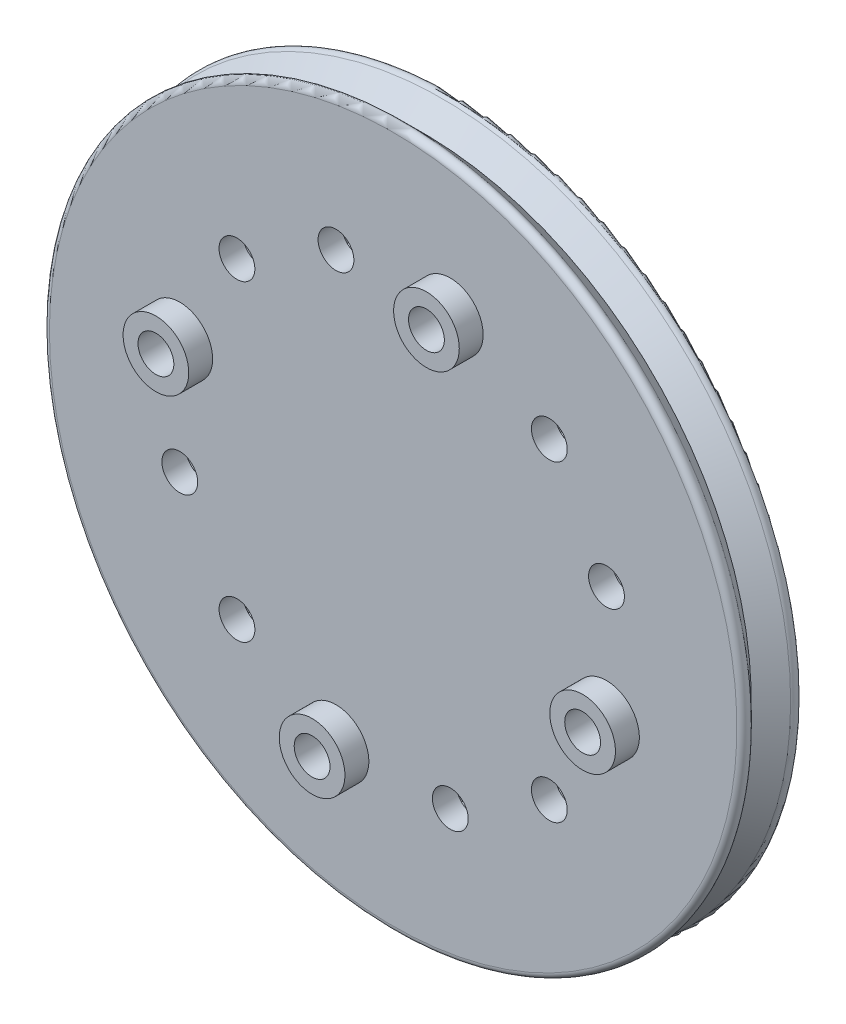
SolidWorks part; units mm, degrees
ref_plane "Front Plane" through (0, 0, 0) normal (0, 0, 1) x (1, 0, 0)
ref_plane "Top Plane" through (0, 0, 0) normal (0, 1, 0) x (1, 0, 0)
ref_plane "Right Plane" through (0, 0, 0) normal (1, 0, 0) x (0, 0, -1)
sketch "草图1" plane through (0, 0, 0) normal (0, 0, 1) x (1, 0, 0)
  circle A0 centre (0, 0) radius 30
  dimension "D1" = 60
sketch "草图2" plane through (0, 0, 0) normal (0, 1, 0) x (1, 0, 0)
  line L0 (0, 2.5) -> (0, -2.5) construction
  line L1 (0, -2.5) -> (30, -2.5)
  line L2 (30, -2.5) -> (27.5, 0)
  line L3 (-30, 0) -> (30, 0) construction
  line L4 (27.5, 0) -> (30, 2.5)
  line L5 (30, 2.5) -> (0, 2.5)
  line L6 (30, 2.5) -> (30, -2.5) construction
  line L7 (0, 2.5) -> (0, -2.5)
  point P8 (0, 0)
  dimension "D1" = 30
  dimension "D2" = 5
revolve "旋转1" add sketch "草图2" angle 360 about L7
sketch "草图3" plane through (0, 0, 2.5) normal (0, 0, 1) x (1, 0, 0)
  line L0 (4.7882, 17.8696) -> (0, 0) construction
  line L1 (0, 0) -> (0, 22.4622) construction
  circle A0 centre (4.7882, 17.8696) radius 2.75
  dimension "D2" = 5.5
  dimension "D1" = 18.5
  dimension "D3" = 15
extrude "凸台-拉伸1" add sketch "草图3" along normal blind 2
pattern_circular "阵列(圆周)1" count 4 over 360 about axis through (0, 0, 0) along (0, 0, 1) of "凸台-拉伸1"
sketch "草图7" plane through (0, 0, -2.5) normal (0, 0, -1) x (-1, 0, 0)
  line L0 (0, -1000) -> (0, 49000) construction
  line L1 (0, 0) -> (4.7882, 17.8696) construction
  circle A0 centre (4.7882, 17.8696) radius 1.5
  circle A1 centre (0, 0) radius 18.5 construction
  point P7 (-4.7882, 17.8696)
  dimension "D1" = 3
  dimension "D2" = 15
extrude "切除-拉伸3" cut sketch "草图7" against normal blind 10
sketch "草图8" plane through (0, 0, -2.5) normal (0, 0, -1) x (-1, 0, 0)
  line L0 (3.9663, 14.8024) -> (0, 0) construction
  line L1 (3.9663, 14.8024) -> (7.0335, 15.6243)
  line L2 (7.0335, 15.6243) -> (7.8554, 18.6915)
  line L3 (7.8554, 18.6915) -> (5.61, 20.9369)
  line L4 (5.61, 20.9369) -> (2.5428, 20.115)
  line L5 (2.5428, 20.115) -> (1.7209, 17.0478)
  line L6 (1.7209, 17.0478) -> (3.9663, 14.8024)
  circle A0 centre (4.7882, 17.8696) radius 2.75 construction
  dimension "D1" = 5.5
extrude "切除-拉伸4" cut sketch "草图8" against normal blind 3
pattern_circular "阵列(圆周)3" count 3 every 30 about axis through (0, 0, 0) along (0, 0, 1) of "切除-拉伸4", "切除-拉伸3"
pattern_circular "阵列(圆周)4" count 4 over 360 about axis through (0, 0, 2.5) along (0, 0, -1) of "阵列(圆周)3", "切除-拉伸3", "切除-拉伸4"
fillet "圆角1" radius 0.5 2 edges at (-30, 0, 2.5) (-30, 0, -2.5)
